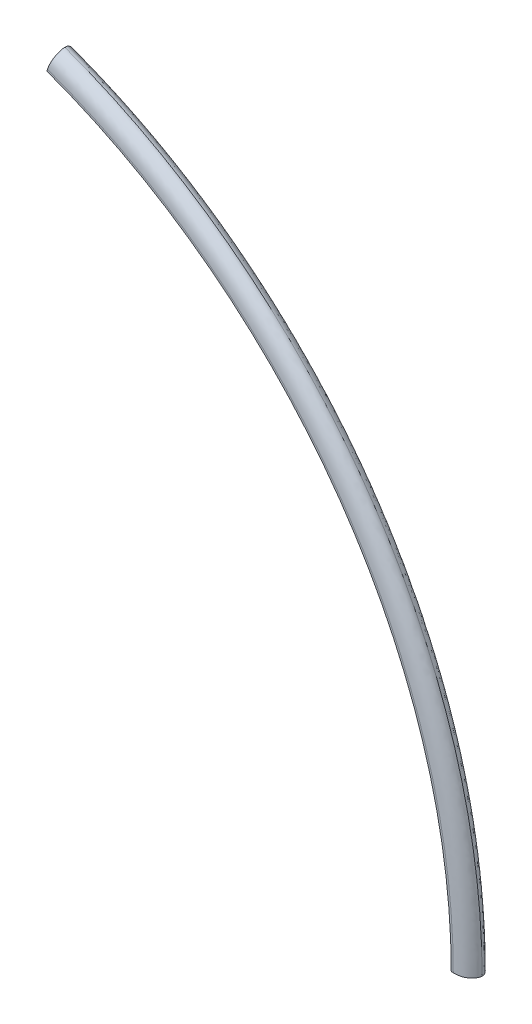
SolidWorks part; units mm, degrees
ref_plane "前视基准面" through (0, 0, 0) normal (0, 0, 1) x (1, 0, 0)
ref_plane "上视基准面" through (0, 0, 0) normal (0, 1, 0) x (1, 0, 0)
ref_plane "右视基准面" through (0, 0, 0) normal (1, 0, 0) x (0, 0, -1)
sketch "草图1" plane through (0, 0, 0) normal (0, 0, 1) x (1, 0, 0)
  line L0 (0, 0) -> (213, 0) construction
  line L1 (0, 0) -> (72.8503, 200.1545) construction
  arc A0 (213, 0) -> (72.8503, 200.1545) centre (0, 0) ccw
  dimension "D1" = 426
  dimension "D2" = 70
ref_plane "基准面1" through (213, 0, 0) normal (0, 1, 0) x (1, 0, 0)
sketch "草图2" plane through (213, 0, 0) normal (0, 1, 0) x (1, 0, 0)
  line L0 (-213, 0) -> (0, 0) construction
  line L1 (0.35, -3) -> (-0.35, -3)
  line L2 (0.35, -3) -> (0.35, 3) construction
  line L3 (0.35, 3) -> (-0.35, 3)
  line L4 (-0.35, -3) -> (-0.35, 3)
  line L5 (0.35, -3) -> (-0.35, 3) construction
  line L6 (0.35, 3) -> (-0.35, -3) construction
  line L9 (0, 0) -> (7.05, 0) construction
  line L10 (0.35, 3) -> (0.35, 4)
  line L11 (1.05, -4) -> (0.35, -4)
  line L13 (1.05, 4) -> (0.35, 4)
  line L14 (0.35, -4) -> (0.35, 4) construction
  line L15 (1.05, -4) -> (0.35, 4) construction
  line L16 (1.05, 4) -> (0.35, -4) construction
  line L17 (0.35, -4) -> (0.35, -3)
  line L18 (4.4258, 4) -> (0.2742, 4) construction
  line L19 (7.05, -0.9472) -> (7.05, 0.9472) construction
  spline S0 degree 3 poles (1.05, 4) (4.1669, 4) (5.6598, 2.6698) (7.05, 0.8905) (7.05, 0) knots 0 0 0 0 0.756596 1 1 1 1
  spline S1 degree 3 poles (1.05, -4) (4.1669, -4) (5.6598, -2.6698) (7.05, -0.8905) (7.05, 0) knots 0 0 0 0 0.756596 1 1 1 1
  point P0 (0, 0)
  point P8 (0.7, 0)
  dimension "D1" = 6
  dimension "D2" = 0.7
  dimension "D3" = 8
  dimension "D4" = 0.7
  dimension "D5" = 6
sweep "扫描1" add profiles "草图2" path "草图1"
ref_plane "基准面2" through (0, 0, 0) normal (-0.5736, 0.8192, 0) x (0, 0, 1)
